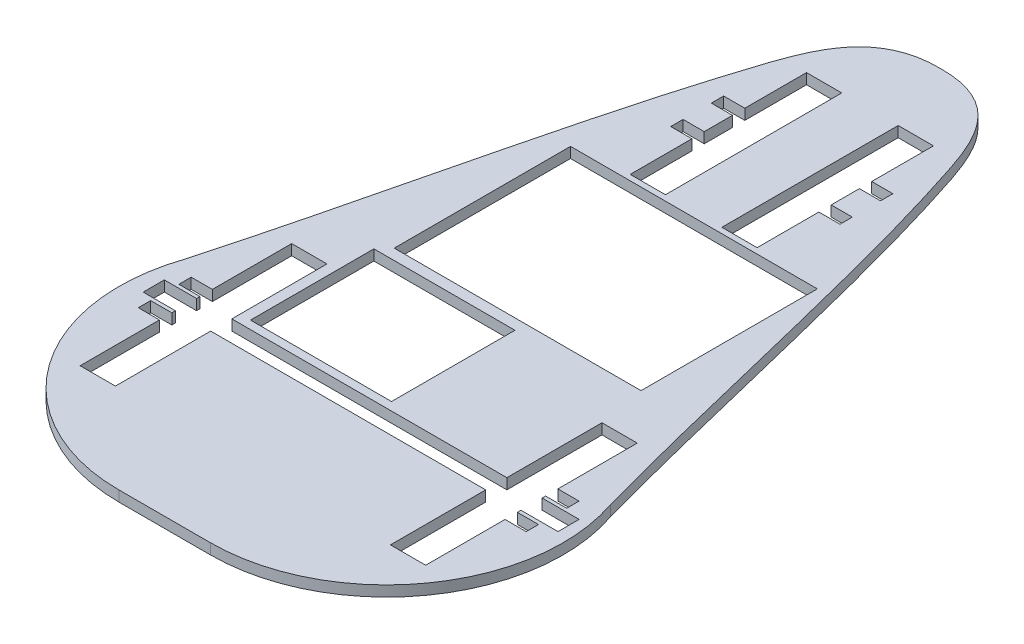
SolidWorks part; units mm, degrees
ref_plane "Front Plane" through (0, 0, 0) normal (0, 0, 1) x (1, 0, 0)
ref_plane "Top Plane" through (0, 0, 0) normal (0, 1, 0) x (1, 0, 0)
ref_plane "Right Plane" through (0, 0, 0) normal (1, 0, 0) x (0, 0, -1)
sketch "Sketch1" plane through (0, 0, 0) normal (0, 1, 0) x (1, 0, 0)
  line L0 (54.9211, 210.7172) -> (54.9211, -9.2828) construction
  line L1 (41.947, -9.2828) -> (67.8952, -9.2828)
  line L5 (-0.0789, 53.2172) -> (5.9211, 53.2172)
  line L6 (5.9211, 75.7172) -> (15.9211, 75.7172)
  line L7 (54.9211, -9.2828) -> (64.9211, -9.2828)
  line L8 (54.9211, -9.2828) -> (44.9211, -9.2828)
  line L9 (5.9211, 75.7172) -> (5.9211, 15.7172)
  line L10 (5.9211, 15.7172) -> (15.9211, 15.7172)
  line L11 (15.9211, 75.7172) -> (15.9211, 15.7172)
  line L12 (5.9211, 75.7172) -> (15.9211, 15.7172) construction
  line L13 (5.9211, 15.7172) -> (15.9211, 75.7172) construction
  line L18 (-0.0789, 49.7172) -> (5.9211, 41.7172) construction
  line L19 (-0.0789, 41.7172) -> (5.9211, 49.7172) construction
  line L20 (-0.0789, 53.2172) -> (-0.0789, 49.7172)
  line L21 (-0.0789, 49.7172) -> (5.9211, 49.7172)
  line L22 (5.9211, 53.2172) -> (5.9211, 49.7172)
  line L23 (-0.0789, 41.7172) -> (5.9211, 41.7172)
  line L24 (-0.0789, 41.7172) -> (-0.0789, 38.2172)
  line L25 (-0.0789, 38.2172) -> (5.9211, 38.2172)
  line L26 (5.9211, 41.7172) -> (5.9211, 38.2172)
  line L27 (109.9211, 41.7172) -> (109.9211, 38.2172)
  line L28 (109.9211, 38.2172) -> (103.9211, 38.2172)
  line L29 (103.9211, 41.7172) -> (103.9211, 38.2172)
  line L30 (109.9211, 41.7172) -> (103.9211, 41.7172)
  line L31 (109.9211, 53.2172) -> (109.9211, 49.7172)
  line L32 (109.9211, 49.7172) -> (103.9211, 49.7172)
  line L33 (103.9211, 53.2172) -> (103.9211, 49.7172)
  line L34 (109.9211, 53.2172) -> (103.9211, 53.2172)
  line L35 (103.9211, 15.7172) -> (93.9211, 15.7172)
  line L36 (93.9211, 75.7172) -> (93.9211, 15.7172)
  line L37 (103.9211, 75.7172) -> (93.9211, 75.7172)
  line L38 (103.9211, 75.7172) -> (103.9211, 15.7172)
  line L39 (30.9211, 173.2172) -> (36.9211, 173.2172)
  line L40 (36.9211, 190.7172) -> (46.9211, 190.7172)
  line L41 (36.9211, 190.7172) -> (36.9211, 140.7172)
  line L42 (36.9211, 140.7172) -> (46.9211, 140.7172)
  line L43 (46.9211, 190.7172) -> (46.9211, 140.7172)
  line L44 (36.9211, 190.7172) -> (46.9211, 140.7172) construction
  line L45 (36.9211, 140.7172) -> (46.9211, 190.7172) construction
  line L47 (21.5766, 139.1342) -> (91.5766, 139.1342)
  line L48 (30.9211, 173.2172) -> (30.9211, 169.7172)
  line L49 (30.9211, 169.7172) -> (36.9211, 169.7172)
  line L50 (36.9211, 173.2172) -> (36.9211, 169.7172)
  line L51 (30.9211, 161.7172) -> (36.9211, 161.7172)
  line L52 (30.9211, 161.7172) -> (30.9211, 158.2172)
  line L53 (30.9211, 158.2172) -> (36.9211, 158.2172)
  line L54 (36.9211, 161.7172) -> (36.9211, 158.2172)
  line L55 (78.9211, 161.7172) -> (78.9211, 158.2172)
  line L56 (78.9211, 158.2172) -> (72.9211, 158.2172)
  line L57 (72.9211, 161.7172) -> (72.9211, 158.2172)
  line L58 (78.9211, 161.7172) -> (72.9211, 161.7172)
  line L59 (78.9211, 173.2172) -> (78.9211, 169.7172)
  line L60 (78.9211, 169.7172) -> (72.9211, 169.7172)
  line L61 (72.9211, 173.2172) -> (72.9211, 169.7172)
  line L62 (78.9211, 173.2172) -> (72.9211, 173.2172)
  line L63 (72.9211, 140.7172) -> (62.9211, 140.7172)
  line L64 (62.9211, 190.7172) -> (62.9211, 140.7172)
  line L65 (72.9211, 190.7172) -> (62.9211, 190.7172)
  line L66 (72.9211, 190.7172) -> (72.9211, 140.7172)
  line L67 (21.5766, 139.1342) -> (21.5766, 89.1342)
  line L68 (21.5766, 89.1342) -> (91.5766, 89.1342)
  line L69 (91.5766, 139.1342) -> (91.5766, 89.1342)
  line L70 (18.8707, 86.0824) -> (58.8707, 86.0824)
  line L71 (18.8707, 86.0824) -> (18.8707, 51.0824)
  line L72 (18.8707, 51.0824) -> (58.8707, 51.0824)
  line L73 (58.8707, 86.0824) -> (58.8707, 51.0824)
  line L74 (-3.2215, 48.7364) -> (114.4207, 48.7364)
  line L75 (-3.2215, 48.7364) -> (-3.2215, 42.7364)
  line L76 (-3.2215, 42.7364) -> (114.4207, 42.7364)
  line L77 (114.4207, 48.7364) -> (114.4207, 42.7364)
  arc A0 (41.947, -9.2828) -> (-5.4028, 56.7793) centre (41.947, 40.7172) cw
  arc A1 (67.8952, -9.2828) -> (115.245, 56.7793) centre (67.8952, 40.7172) ccw
  spline S0 degree 3 poles (54.9211, 210.7172) (54.0308, 210.7172) (36.7248, 210.3077) (26.6736, 181.7821) (12.5146, 130.3071) (2.5819, 85.5886) (-5.4028, 56.7793) knots 0 0 0 0 0.011068 0.221366 0.459883 1 1 1 1
  spline S1 degree 3 poles (54.9211, 210.7172) (55.8114, 210.7172) (73.1174, 210.3077) (83.1686, 181.7821) (97.3276, 130.3071) (107.2603, 85.5886) (115.245, 56.7793) knots 0 0 0 0 0.011068 0.221366 0.459883 1 1 1 1
  point P4 (2.9211, 45.7172)
  point P21 (120, 0)
  point P24 (10.9211, 45.7172)
  point P50 (41.9211, 165.7172)
  point P81 (114.4207, 42.7364)
  dimension "D6" = 10
  dimension "D7" = 50
  dimension "D10" = 8
  dimension "D2" = 173.1277
  dimension "D1" = 220
  dimension "D3" = 60.3239
  dimension "D4" = 10
  dimension "D5" = 10
  dimension "D8" = 60
  dimension "D9" = 6
  dimension "D11" = 25
  dimension "D12" = 8
  dimension "D13" = 0
  dimension "D14" = 22.5
  dimension "D15" = 3.5
  dimension "D16" = 0
  dimension "D17" = 22.5
  dimension "D18" = 39
  dimension "D19" = 6
  dimension "D20" = 10
  dimension "D21" = 50
  dimension "D22" = 20
  dimension "D23" = 8
  dimension "D24" = 3.5
  dimension "D25" = 17.5
  dimension "D26" = 8
  dimension "D27" = 0
  dimension "D28" = 6
  dimension "D29" = 70
  dimension "D30" = 50
  dimension "D31" = 35
  dimension "D32" = 40
  dimension "D33" = 6
extrude "Boss-Extrude1" add sketch "Sketch1" along normal blind 3 contours L0 S0 A0 L1 | S1 L0 L1 A1
